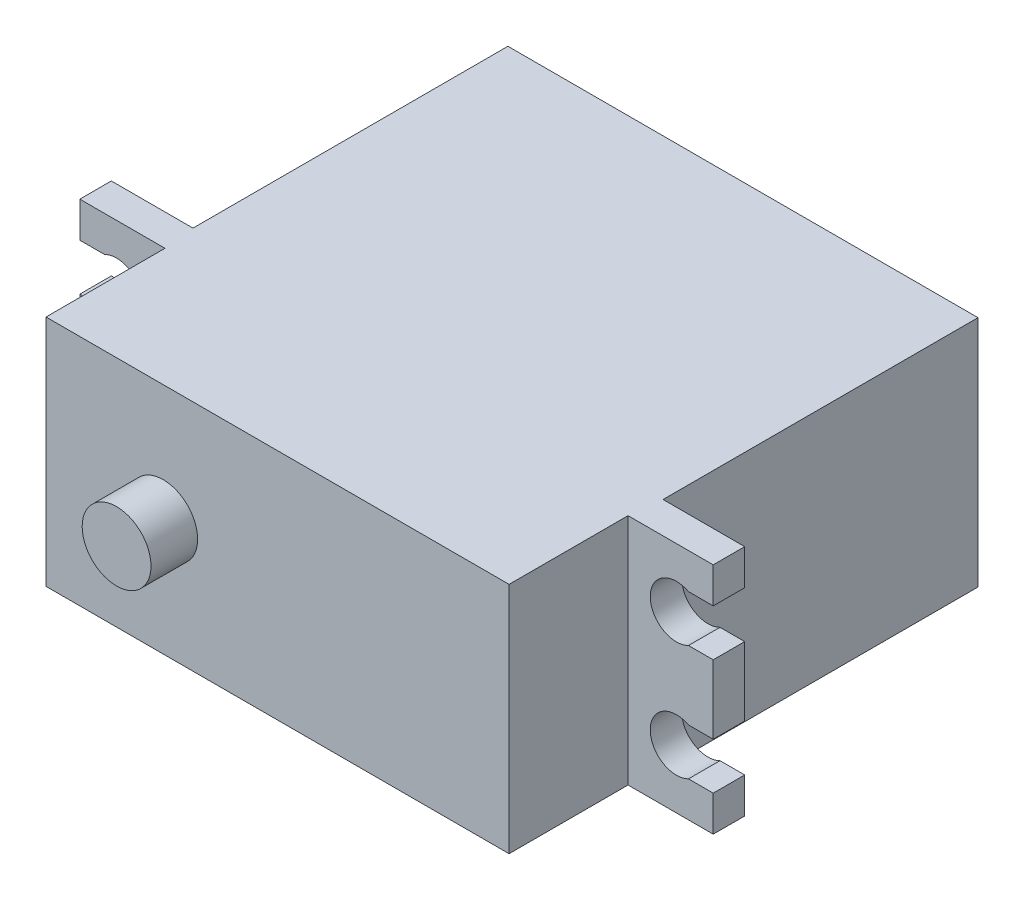
SolidWorks part; units mm, degrees
ref_plane "Front Plane" through (0, 0, 0) normal (0, 0, 1) x (1, 0, 0)
ref_plane "Top Plane" through (0, 0, 0) normal (0, 1, 0) x (1, 0, 0)
ref_plane "Right Plane" through (0, 0, 0) normal (1, 0, 0) x (0, 0, -1)
other "Bounding Box"
ref_plane "Default Plane" through (-8.9266, -12.7485, 0) normal (-0.1736, 0.9848, 0) x (0.9848, 0.1736, 0)
sketch "Sketch1" plane through (0, 0, 0) normal (0, 1, 0) x (1, 0, 0)
  line L1 (20.15, -13.5) -> (-20.15, -13.5)
  line L2 (20.15, -13.5) -> (20.15, 13.5)
  line L3 (20.15, 13.5) -> (-20.15, 13.5)
  line L4 (-20.15, -13.5) -> (-20.15, 13.5)
  line L5 (20.15, -13.5) -> (-20.15, 13.5) construction
  line L6 (20.15, 13.5) -> (-20.15, -13.5) construction
  point P0 (0, 0)
  dimension "D1" = 40.3
  dimension "D2" = 27
extrude "Boss-Extrude1" add sketch "Sketch1" along normal blind 20
sketch "Sketch2" plane through (0, 0, 13.5) normal (0, 0, 1) x (1, 0, 0)
  line L0 (-20.15, 10) -> (20.15, 10) construction
  line L1 (-20.15, 20) -> (-20.15, 0) construction
  line L2 (20.15, 20) -> (20.15, 0) construction
  line L3 (0, 0) -> (0, 20) construction
  line L4 (-20.15, 20) -> (20.15, 20) construction
  line L5 (-20.15, 20) -> (20.15, 20)
  line L6 (27.15, 0) -> (-27.15, 0)
  line L7 (27.15, 0) -> (27.15, 20)
  line L8 (27.15, 20) -> (-27.15, 20)
  line L9 (-27.15, 0) -> (-27.15, 20)
  line L10 (27.15, 0) -> (-27.15, 20) construction
  line L11 (27.15, 20) -> (-27.15, 0) construction
  line L13 (24, 5.05) -> (-24, 5.05)
  line L14 (24, 5.05) -> (24, 14.95)
  line L15 (24, 14.95) -> (-24, 14.95)
  line L16 (-24, 5.05) -> (-24, 14.95)
  line L17 (24, 5.05) -> (-24, 14.95) construction
  line L18 (24, 14.95) -> (-24, 5.05) construction
  line L19 (-24, 12.95) -> (-30.3, 12.95)
  line L20 (-24, 12.95) -> (-24, 16.95)
  line L21 (-24, 16.95) -> (-30.3, 16.95)
  line L22 (-30.3, 12.95) -> (-30.3, 16.95)
  line L23 (-24, 12.95) -> (-30.3, 16.95) construction
  line L24 (-24, 16.95) -> (-30.3, 12.95) construction
  line L29 (-24, 3.05) -> (-30.3, 3.05)
  line L30 (-24, 3.05) -> (-24, 7.05)
  line L31 (-24, 7.05) -> (-30.3, 7.05)
  line L32 (-30.3, 3.05) -> (-30.3, 7.05)
  line L33 (-24, 3.05) -> (-30.3, 7.05) construction
  line L34 (-24, 7.05) -> (-30.3, 3.05) construction
  line L35 (24, 16.95) -> (30.3, 16.95)
  line L36 (24, 16.95) -> (24, 12.95)
  line L37 (24, 12.95) -> (30.3, 12.95)
  line L38 (30.3, 16.95) -> (30.3, 12.95)
  line L39 (24, 16.95) -> (30.3, 12.95) construction
  line L40 (24, 12.95) -> (30.3, 16.95) construction
  line L41 (24, 7.05) -> (30.3, 7.05)
  line L42 (24, 7.05) -> (24, 3.05)
  line L43 (24, 3.05) -> (30.3, 3.05)
  line L44 (30.3, 7.05) -> (30.3, 3.05)
  line L45 (24, 7.05) -> (30.3, 3.05) construction
  line L46 (24, 3.05) -> (30.3, 7.05) construction
  circle A0 centre (-24, 14.95) radius 2.25
  circle A1 centre (-24, 5.05) radius 2.25
  circle A2 centre (24, 5.05) radius 2.25
  circle A3 centre (24, 14.95) radius 2.25
  point P11 (0, 10)
  point P16 (0, 10)
  point P25 (-27.15, 14.95)
  point P30 (-27.15, 5.05)
  point P35 (27.15, 14.95)
  point P40 (27.15, 5.05)
  line M3 (-20.15, 0) -> (20.15, 0)
  line M4 (20.15, 0) -> (20.15, 20)
  line M5 (20.15, 20) -> (-20.15, 20)
  line M6 (-20.15, 20) -> (-20.15, 0)
  dimension "D4" = 4.5
  dimension "D1" = 54.3
  dimension "D2" = 48
  dimension "D3" = 9.9
  dimension "D5" = 4
extrude "Boss-Extrude2" add sketch "Sketch2" along normal blind 2.7 contours L13 M4 M6 M3 | A1 L29 L9 L6 L13 M6 | L15 L13 M4 M6 | A1 L13 L15 A0 L16 M6 | A1 L16 A0 L19 L9 L31 | L15 M4 M5 M6 | A0 L15 L8 L9 L21 M6 | A3 L35 L7 L8 L15 M4 | A3 L14 A2 L41 L7 L37 | A2 L13 L6 L7 L43 M4 | A3 L15 L13 A2 L14 M4
sketch "Sketch3" plane through (0, 0, 16.2) normal (0, 0, 1) x (1, 0, 0)
  line L0 (-27.15, 10) -> (27.15, 10) construction
  line L1 (-27.15, 7.05) -> (-27.15, 12.95) construction
  line L2 (27.15, 7.05) -> (27.15, 12.95) construction
  line L3 (0, 20) -> (0, 0) construction
  line L4 (27.15, 20) -> (-27.15, 20) construction
  line L5 (27.15, 20) -> (-27.15, 20)
  line L6 (19.85, 0) -> (-19.85, 0)
  line L7 (19.85, 0) -> (19.85, 20)
  line L8 (19.85, 20) -> (-19.85, 20)
  line L9 (-19.85, 0) -> (-19.85, 20)
  line L10 (19.85, 0) -> (-19.85, 20) construction
  line L11 (19.85, 20) -> (-19.85, 0) construction
  point P11 (0, 10)
  dimension "D2" = 39.7
extrude "Boss-Extrude3" add sketch "Sketch3" along normal blind 10.2 contours L7 L6 L9 L8
sketch "Sketch4" plane through (0, 0, 26.4) normal (0, 0, 1) x (1, 0, 0)
  line L0 (-27.15, 10) -> (27.15, 10) construction
  line L1 (-27.15, 7.05) -> (-27.15, 12.95) construction
  line L2 (27.15, 7.05) -> (27.15, 12.95) construction
  arc A0 (-25.0308, 12.95) -> (-25.0308, 16.95) centre (-24, 14.95) ccw construction
  arc A1 (-25.0308, 12.95) -> (-25.0308, 16.95) centre (-24, 14.95) ccw
  circle A2 centre (-9.8, 10) radius 2.95
  dimension "D2" = 5.9
  dimension "D1" = 14.2
extrude "Boss-Extrude4" add sketch "Sketch4" along normal blind 4 contours A2 L0 | L0 A2
sketch "Sketch5" plane through (-20.15, 0, 0) normal (-1, 0, 0) x (0, 0, 1)
  line L0 (-13.5, 10) -> (6.1644, 10) construction
  line L1 (-6.9171, 4.3103) -> (-10.4185, 4.3103)
  line L2 (-6.9171, 4.3103) -> (-6.9171, 15.6897)
  line L3 (-6.9171, 15.6897) -> (-10.4185, 15.6897)
  line L4 (-10.4185, 4.3103) -> (-10.4185, 15.6897)
  line L5 (-6.9171, 4.3103) -> (-10.4185, 15.6897) construction
  line L6 (-6.9171, 15.6897) -> (-10.4185, 4.3103) construction
  line L7 (-13.5, 20) -> (-13.5, 0) construction
  point P0 (-8.6678, 10)
  dimension "D1" = 11.3794
  dimension "D2" = 3.5014
  dimension "D3" = 4.8322
extrude "Boss-Extrude5" add sketch "Sketch5" along normal blind 4
